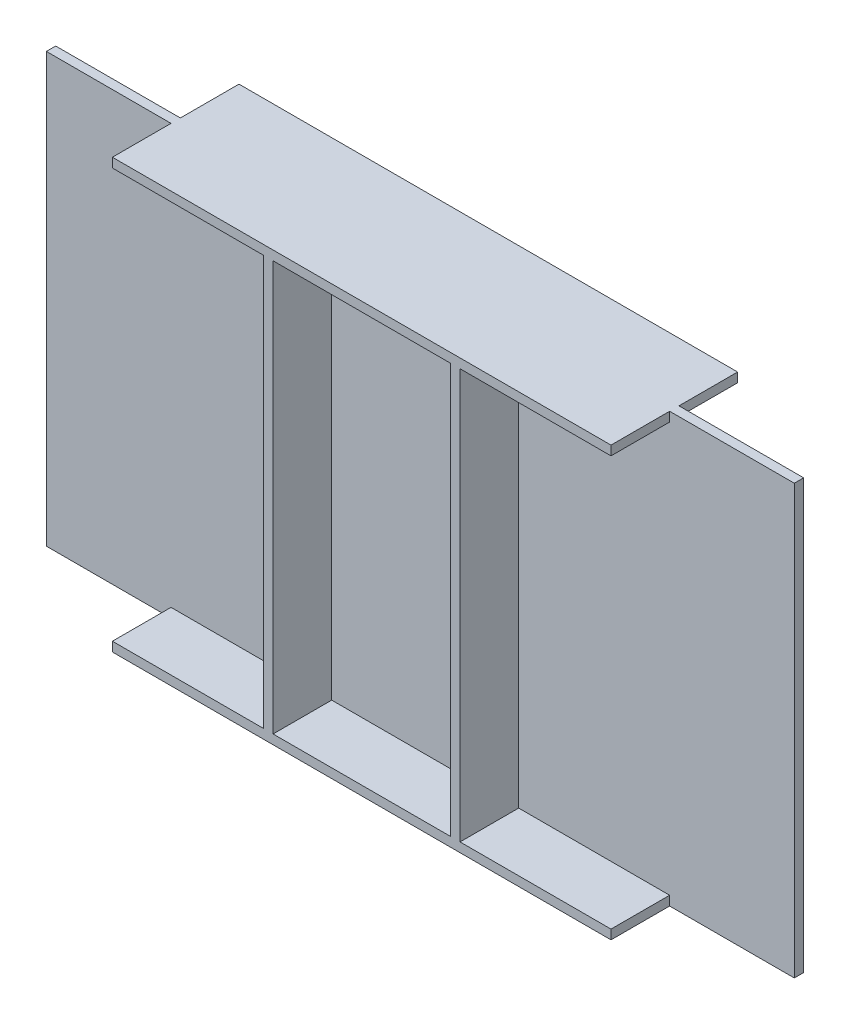
SolidWorks part; units mm, degrees
ref_plane "前视基准面" through (0, 0, 0) normal (0, 0, 1) x (1, 0, 0)
ref_plane "上视基准面" through (0, 0, 0) normal (0, 1, 0) x (1, 0, 0)
ref_plane "右视基准面" through (0, 0, 0) normal (1, 0, 0) x (0, 0, -1)
sketch "草图1" plane through (0, 0, 0) normal (0, 0, 1) x (1, 0, 0)
  line L1 (0, 0) -> (960, 0)
  line L2 (0, 0) -> (0, 550)
  line L3 (0, 550) -> (960, 550)
  line L4 (960, 0) -> (960, 550)
  dimension "D1" = 960
  dimension "D2" = 550
extrude "凸台-拉伸1" add sketch "草图1" along normal blind 12
sketch "草图2" plane through (0, 550, 0) normal (0, 1, 0) x (1, 0, 0)
  line L0 (480, -1012) -> (480, 48988) construction
  line L1 (960, -12) -> (0, -12) construction
  line L2 (-1000, -6) -> (49000, -6) construction
  line L3 (0, -12) -> (0, 0) construction
  line L5 (160, 75.25) -> (800, 75.25)
  line L6 (160, 75.25) -> (160, -87.25)
  line L7 (160, -87.25) -> (800, -87.25)
  line L8 (800, 75.25) -> (800, -87.25)
  point P5 (480, -12)
  point P10 (0, -6)
  dimension "D1" = 640
  dimension "D2" = 162.5
extrude "凸台-拉伸2" add sketch "草图2" against normal blind 12
sketch "草图3" plane through (0, 0, 0) normal (0, -1, 0) x (1, 0, 0)
  line L1 (160, 87.25) -> (800, 87.25)
  line L2 (160, 87.25) -> (160, -75.25)
  line L3 (160, -75.25) -> (800, -75.25)
  line L4 (800, 87.25) -> (800, -75.25)
extrude "凸台-拉伸3" add sketch "草图3" against normal blind 12
sketch "草图4" plane through (0, 0, -75.25) normal (0, 0, -1) x (-1, 0, 0)
  line L0 (-160, 538) -> (-800, 538) construction
  line L1 (-606.25, 538) -> (-593.75, 538)
  line L2 (-606.25, 538) -> (-606.25, 12)
  line L3 (-606.25, 12) -> (-593.75, 12)
  line L4 (-593.75, 538) -> (-593.75, 12)
  line L5 (-160, 12) -> (-800, 12) construction
  line L6 (-366.25, 538) -> (-353.75, 538)
  line L7 (-366.25, 538) -> (-366.25, 12)
  line L8 (-366.25, 12) -> (-353.75, 12)
  line L9 (-353.75, 538) -> (-353.75, 12)
  line L10 (-480, -450) -> (-480, 49550) construction
  line L11 (-800, 550) -> (-160, 550) construction
  line L12 (-600, -450) -> (-600, 49550) construction
  line L13 (-360, -450) -> (-360, 49550) construction
  point P17 (-480, 550)
  dimension "D1" = 12.5
  dimension "D2" = 12.5
  dimension "D3" = 120
  dimension "D4" = 120
extrude "凸台-拉伸4" add sketch "草图4" against normal blind 162.5
